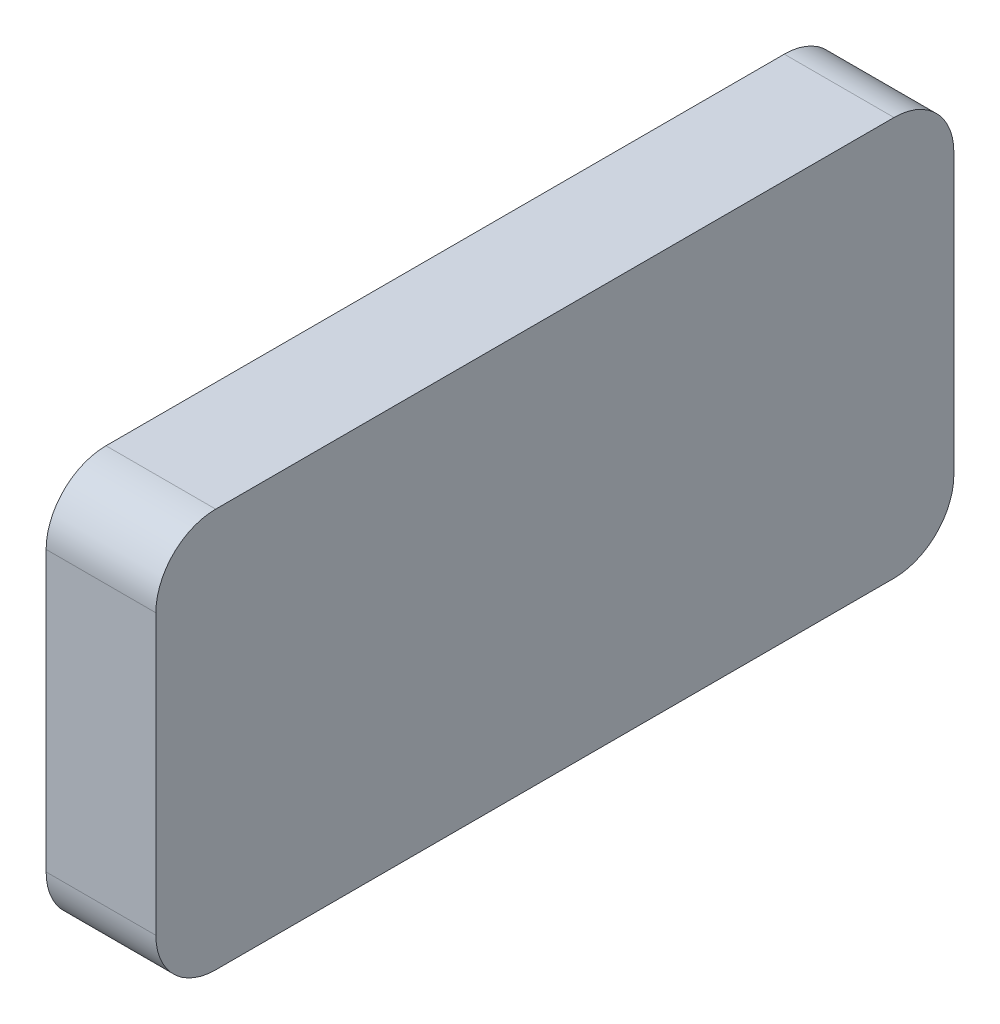
SolidWorks part; units mm, degrees
ref_plane "Front Plane" through (0, 0, 0) normal (0, 0, 1) x (1, 0, 0)
ref_plane "Top Plane" through (0, 0, 0) normal (0, 1, 0) x (1, 0, 0)
ref_plane "Right Plane" through (0, 0, 0) normal (1, 0, 0) x (0, 0, -1)
sketch "Sketch1" plane through (0, 0, 0) normal (1, 0, 0) x (0, 0, -1)
  line L0 (24, 5.8) -> (24, 19.8)
  line L1 (21, 22.8) -> (-13, 22.8)
  line L2 (-16, 19.8) -> (-16, 5.8)
  line L3 (-13, 2.8) -> (21, 2.8)
  arc A0 (21, 2.8) -> (24, 5.8) centre (21, 5.8) ccw
  arc A1 (24, 19.8) -> (21, 22.8) centre (21, 19.8) ccw
  arc A2 (-13, 22.8) -> (-16, 19.8) centre (-13, 19.8) ccw
  arc A3 (-16, 5.8) -> (-13, 2.8) centre (-13, 5.8) ccw
extrude "Driver" add sketch "Sketch1" along normal blind 5.5 from offset 61
